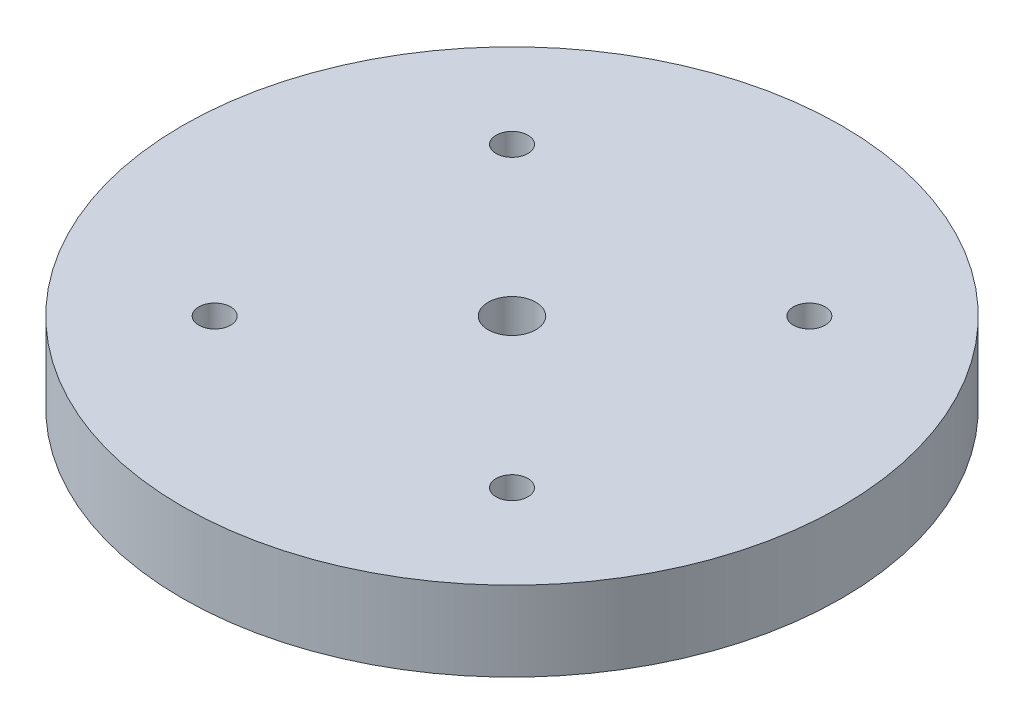
SolidWorks part; units mm, degrees
material "6061 Alloy"
ref_plane "Alzado" through (0, 0, 0) normal (0, 0, 1) x (1, 0, 0)
ref_plane "Planta" through (0, 0, 0) normal (0, 1, 0) x (1, 0, 0)
ref_plane "Vista lateral" through (0, 0, 0) normal (1, 0, 0) x (0, 0, -1)
ref_plane "Plane2" through (0, -209, 0) normal (0, 1, 0) x (1, 0, 0)
sketch "Sketch1" plane through (0, -209, 0) normal (0, 1, 0) x (1, 0, 0)
  circle A0 centre (0, 0) radius 12.4196
  circle A1 centre (0, 0) radius 0.9
  circle A2 centre (5.6, 5.6) radius 0.6
  circle A3 centre (-5.6, 5.6) radius 0.6
  circle A4 centre (-5.6, -5.6) radius 0.6
  circle A5 centre (5.6, -5.6) radius 0.6
extrude "Disco_aponeurosis" add sketch "Sketch1" along normal blind 3
sketch "Sketch2" plane through (0, 0, 0) normal (0, 0, 1) x (1, 0, 0)
  line L0 (0, -209) -> (3, -209)
  line L1 (3, -209) -> (3, -215)
  line L2 (3, -215) -> (1.2, -215)
  line L3 (1.2, -215) -> (0, -215)
  line L4 (0, -215) -> (0, -209)
  line L5 (0, -219) -> (0, -205) construction
revolve "Boca_tendon" add sketch "Sketch2" angle 360 about L5
